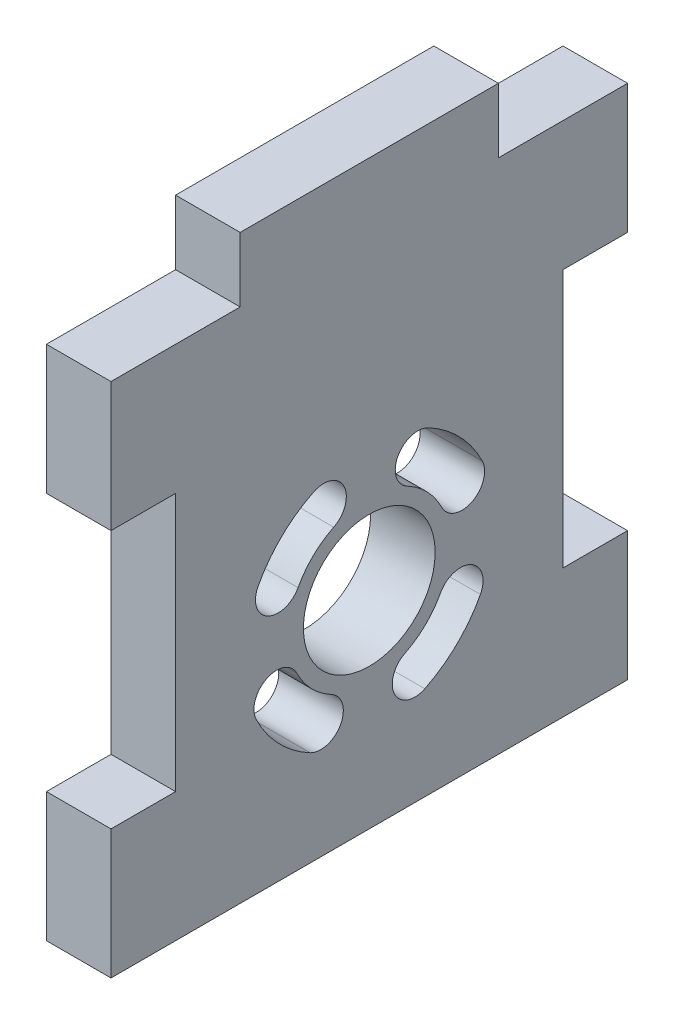
SolidWorks part; units mm, degrees
ref_plane "前视基准面" through (0, 0, 0) normal (0, 0, 1) x (1, 0, 0)
ref_plane "上视基准面" through (0, 0, 0) normal (0, 1, 0) x (1, 0, 0)
ref_plane "右视基准面" through (0, 0, 0) normal (1, 0, 0) x (0, 0, -1)
sketch "草图1" plane through (0, 0, 0) normal (1, 0, 0) x (0, 0, -1)
  line L0 (-30, 40) -> (-40, 40)
  line L1 (0, 0) -> (-40, 0)
  line L2 (0, 0) -> (0, 10)
  line L3 (0, 40) -> (-10, 40)
  line L4 (-40, 0) -> (-40, 10)
  line L5 (0, 30) -> (0, 40)
  line L6 (-30, 40) -> (-30, 45)
  line L7 (-30, 45) -> (-10, 45)
  line L8 (-10, 40) -> (-10, 45)
  line L9 (-40, 30) -> (-35, 30)
  line L11 (-40, 10) -> (-35, 10)
  line L12 (-35, 30) -> (-35, 10)
  line L13 (0, 30) -> (-5, 30)
  line L14 (-40, 30) -> (-40, 40)
  line L15 (0, 10) -> (-5, 10)
  line L16 (-5, 30) -> (-5, 10)
  line L17 (-29, 7) -> (-11, 7) construction
  line L18 (-29, 7) -> (-29, 25) construction
  line L19 (-29, 25) -> (-11, 25) construction
  line L20 (-11, 7) -> (-11, 25) construction
  line L21 (-29, 7) -> (-11, 25) construction
  line L22 (-29, 25) -> (-11, 7) construction
  circle A0 centre (-20, 16) radius 5.1
  arc A1 (-27.0616, 19.7595) -> (-23.527, 23.1805) centre (-20, 16) cw construction
  arc A2 (-24.2986, 24.7513) -> (-28.6063, 20.5819) centre (-20, 16) ccw
  arc A3 (-22.7555, 21.6098) -> (-25.5169, 18.9371) centre (-20, 16) ccw
  arc A4 (-22.7555, 21.6098) -> (-24.2986, 24.7513) centre (-23.527, 23.1805) ccw
  arc A5 (-28.6063, 20.5819) -> (-25.5169, 18.9371) centre (-27.0616, 19.7595) ccw
  arc A6 (-16.2405, 23.0616) -> (-12.8195, 19.527) centre (-20, 16) cw construction
  arc A7 (-11.2487, 20.2986) -> (-15.4181, 24.6063) centre (-20, 16) ccw
  arc A8 (-14.3902, 18.7555) -> (-17.0629, 21.5169) centre (-20, 16) ccw
  arc A9 (-14.3902, 18.7555) -> (-11.2487, 20.2986) centre (-12.8195, 19.527) ccw
  arc A10 (-15.4181, 24.6063) -> (-17.0629, 21.5169) centre (-16.2405, 23.0616) ccw
  arc A11 (-12.9384, 12.2405) -> (-16.473, 8.8195) centre (-20, 16) cw construction
  arc A12 (-15.7014, 7.2487) -> (-11.3937, 11.4181) centre (-20, 16) ccw
  arc A13 (-17.2445, 10.3902) -> (-14.4831, 13.0629) centre (-20, 16) ccw
  arc A14 (-17.2445, 10.3902) -> (-15.7014, 7.2487) centre (-16.473, 8.8195) ccw
  arc A15 (-11.3937, 11.4181) -> (-14.4831, 13.0629) centre (-12.9384, 12.2405) ccw
  arc A16 (-23.7595, 8.9384) -> (-27.1805, 12.473) centre (-20, 16) cw construction
  arc A17 (-28.7513, 11.7014) -> (-24.5819, 7.3937) centre (-20, 16) ccw
  arc A18 (-25.6098, 13.2445) -> (-22.9371, 10.4831) centre (-20, 16) ccw
  arc A19 (-25.6098, 13.2445) -> (-28.7513, 11.7014) centre (-27.1805, 12.473) ccw
  arc A20 (-24.5819, 7.3937) -> (-22.9371, 10.4831) centre (-23.7595, 8.9384) ccw
  point P25 (-25.5638, 21.7484)
  point P35 (-14.2516, 21.5638)
  point P42 (-14.4362, 10.2516)
  point P49 (-25.7484, 10.4362)
  point P54 (-20, 16)
  dimension "D13" = 10.2
  dimension "D16" = 8
  dimension "D17" = 3.5
  dimension "D18" = 1.75
  dimension "D1" = 40
  dimension "D2" = 40
  dimension "D3" = 20
  dimension "D4" = 20
  dimension "D5" = 5
  dimension "D6" = 5
  dimension "D7" = 5
  dimension "D8" = 20
  dimension "D9" = 10
  dimension "D10" = 10
  dimension "D11" = 40
  dimension "D12" = 10
  dimension "D14" = 24
  dimension "D15" = 20
  dimension "D19" = 4
extrude "凸台-拉伸1" add sketch "草图1" along normal blind 5
